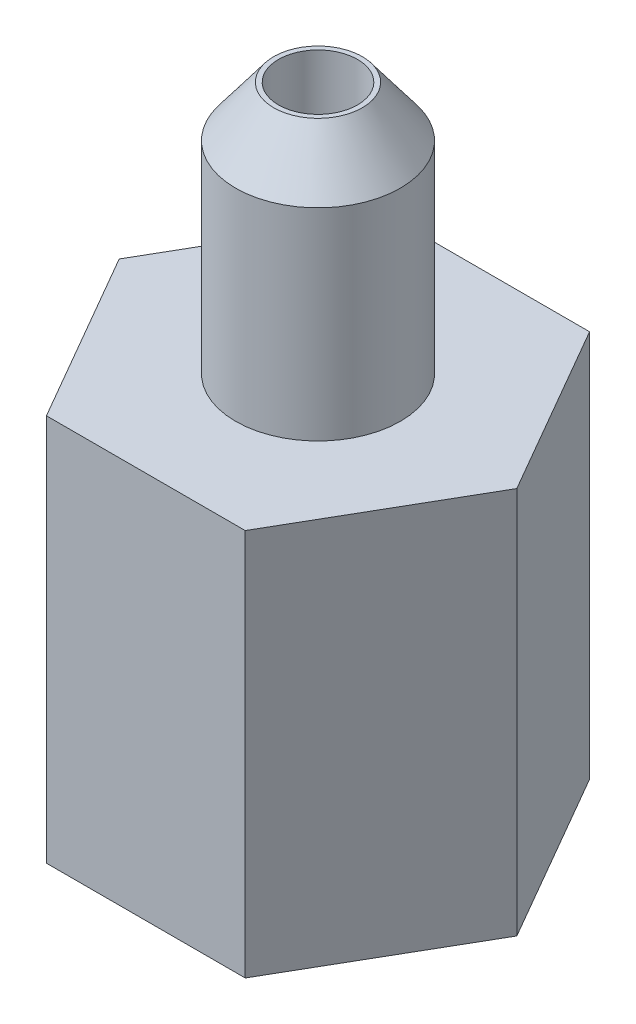
SolidWorks part; units mm, degrees
material "AISI 316 Annealed Stainless Steel Bar (SS)"
ref_plane "Front Plane" through (0, 0, 0) normal (0, 0, 1) x (1, 0, 0)
ref_plane "Top Plane" through (0, 0, 0) normal (0, 1, 0) x (1, 0, 0)
ref_plane "Right Plane" through (0, 0, 0) normal (1, 0, 0) x (0, 0, -1)
sketch "Sketch1" plane through (0, 0, 0) normal (0, 1, 0) x (1, 0, 0)
  line L1 (-10.9985, 0) -> (-5.4993, -9.525)
  line L2 (-5.4993, -9.525) -> (5.4993, -9.525)
  line L3 (5.4993, -9.525) -> (10.9985, 0)
  line L4 (10.9985, 0) -> (5.4993, 9.525)
  line L5 (5.4993, 9.525) -> (-5.4993, 9.525)
  line L6 (-5.4993, 9.525) -> (-10.9985, 0)
  circle A0 centre (0, 0) radius 9.525 construction
  dimension "D1" = 19.05
extrude "Boss-Extrude1" add sketch "Sketch1" along normal blind 21.4376
sketch "Sketch2" plane through (0, 21.4376, 0) normal (0, 1, 0) x (1, 0, 0)
  circle A0 centre (0, 0) radius 4.5593
  dimension "D1" = 9.1186
extrude "Boss-Extrude2" add sketch "Sketch2" along normal blind 13.97
sketch "Sketch3" plane through (0, 35.4076, 0) normal (0, 1, 0) x (1, 0, 0)
  circle A0 centre (0, 0) radius 2.4511
  circle A1 centre (0, 0) radius 19.1727
  dimension "D1" = 4.9022
extrude "Cut-Extrude1" cut sketch "Sketch3" against normal through all draft 37
sketch "Sketch4" plane through (0, 35.4076, 0) normal (0, 1, 0) x (1, 0, 0)
  circle A0 centre (0, 0) radius 2.1844
  dimension "D1" = 4.3688
extrude "Cut-Extrude2" cut sketch "Sketch4" against normal through all
sketch "Sketch5" plane through (0, 0, 0) normal (0, -1, 0) x (1, 0, 0)
  circle A0 centre (0, 0) radius 5.5626
  dimension "D1" = 11.1252
extrude "Cut-Extrude3" cut sketch "Sketch5" against normal offset from surface (15.0876 mm away) 6.35 up to face at (0, 21.4376, 4.5593)
